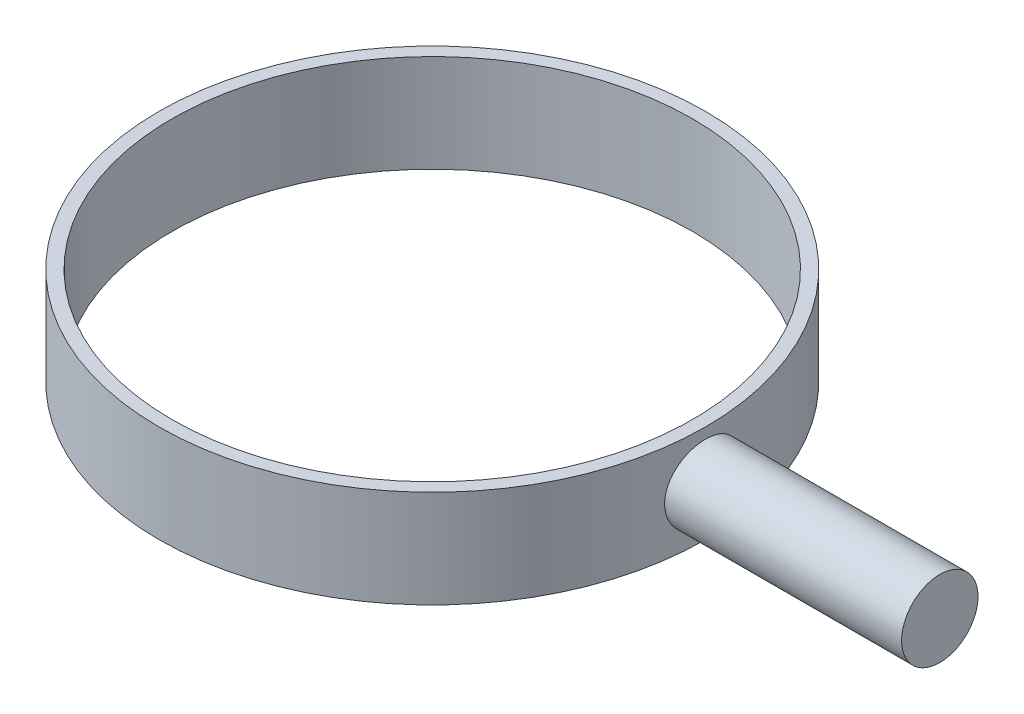
SolidWorks part; units mm, degrees
ref_plane "Front Plane" through (0, 0, 0) normal (0, 0, 1) x (1, 0, 0)
ref_plane "Top Plane" through (0, 0, 0) normal (0, 1, 0) x (1, 0, 0)
ref_plane "Right Plane" through (0, 0, 0) normal (1, 0, 0) x (0, 0, -1)
sketch "Croquis1" plane through (0, 0, 0) normal (0, 1, 0) x (1, 0, 0)
  circle A0 centre (0, 0) radius 50.8254
  circle A1 centre (0, 0) radius 53.34
  dimension "D1" = 101.6508
  dimension "D2" = 106.68
extrude "Saliente-Extruir1" add sketch "Croquis1" along normal mid plane 19.05
sketch "Croquis2" plane through (0, 0, 0) normal (1, 0, 0) x (0, 0, -1)
  circle A0 centre (0, 0) radius 7.4562
  dimension "D1" = 14.9123
extrude "Saliente-Extruir2" add sketch "Croquis2" along normal blind 99.06
sketch "Croquis3" plane through (0, -9.525, 0) normal (0, -1, 0) x (1, 0, 0)
  circle A0 centre (0, 0) radius 50.8254
  dimension "D1" = 101.6508
extrude "Cortar-Extruir1" cut sketch "Croquis3" against normal mid plane 99.06
